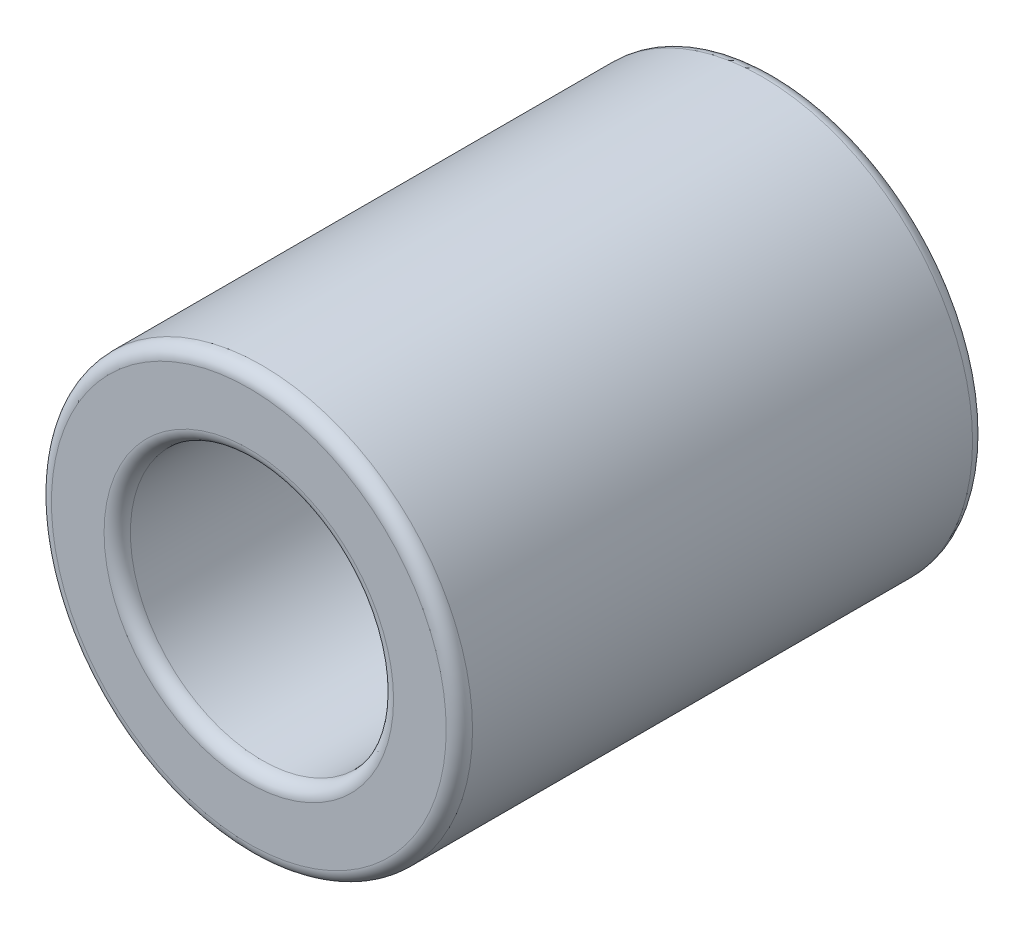
SolidWorks part; units mm, degrees
material "6061-T6 (SS)"
ref_plane "Front Plane" through (0, 0, 0) normal (0, 0, 1) x (1, 0, 0)
ref_plane "Top Plane" through (0, 0, 0) normal (0, 1, 0) x (1, 0, 0)
ref_plane "Right Plane" through (0, 0, 0) normal (1, 0, 0) x (0, 0, -1)
sketch "Sketch1" plane through (0, 0, 0) normal (0, 0, 1) x (1, 0, 0)
  circle A0 centre (0, 0) radius 2.5
  circle A1 centre (0, 0) radius 4
  dimension "D1" = 5
  dimension "D2" = 8
extrude "Boss-Extrude1" add sketch "Sketch1" along normal blind 10 contours A1 A0
fillet "Fillet1" radius 0.25 4 edges at (2.5, 0, 0) (2.5, 0, 10) (4, 0, 0) (4, 0, 10)
